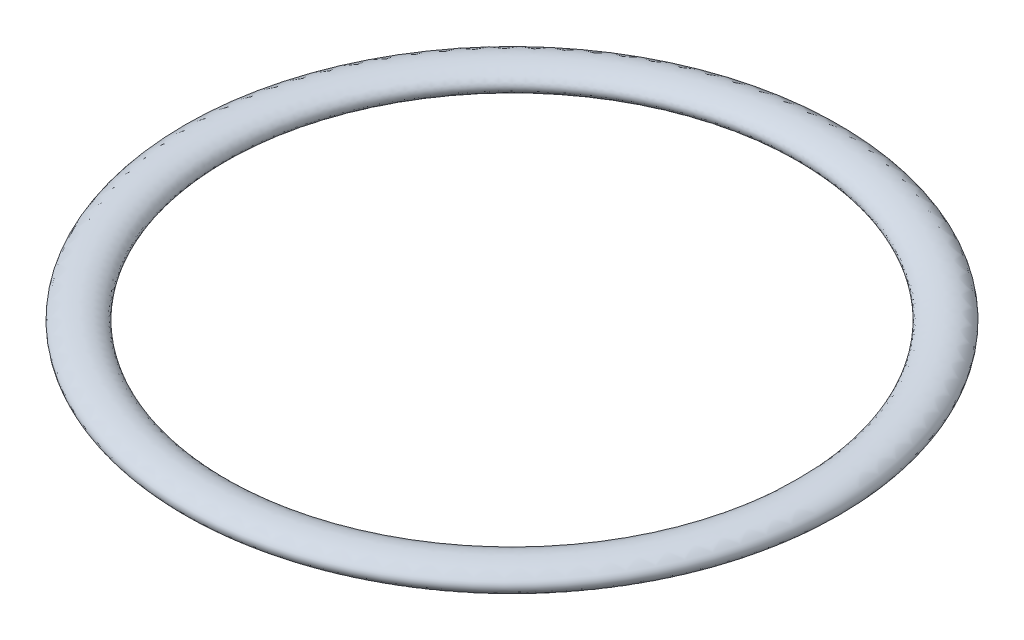
SolidWorks part; units mm, degrees
ref_plane "Front Plane" through (0, 0, 0) normal (0, 0, 1) x (1, 0, 0)
ref_plane "Top Plane" through (0, 0, 0) normal (0, 1, 0) x (1, 0, 0)
ref_plane "Right Plane" through (0, 0, 0) normal (1, 0, 0) x (0, 0, -1)
sketch "Reconstructed nominal axial profile" plane through (0, 0, 0) normal (0, 0, 1) x (1, 0, 0)
  line L0 (0, -500) -> (0, 50) construction
  ellipse E0 centre (18.425, 0) end of major axis (19.8099, 0) minor radius 0.725
revolve "Native revolved geometry" add sketch "Reconstructed nominal axial profile" angle 360 about L0
